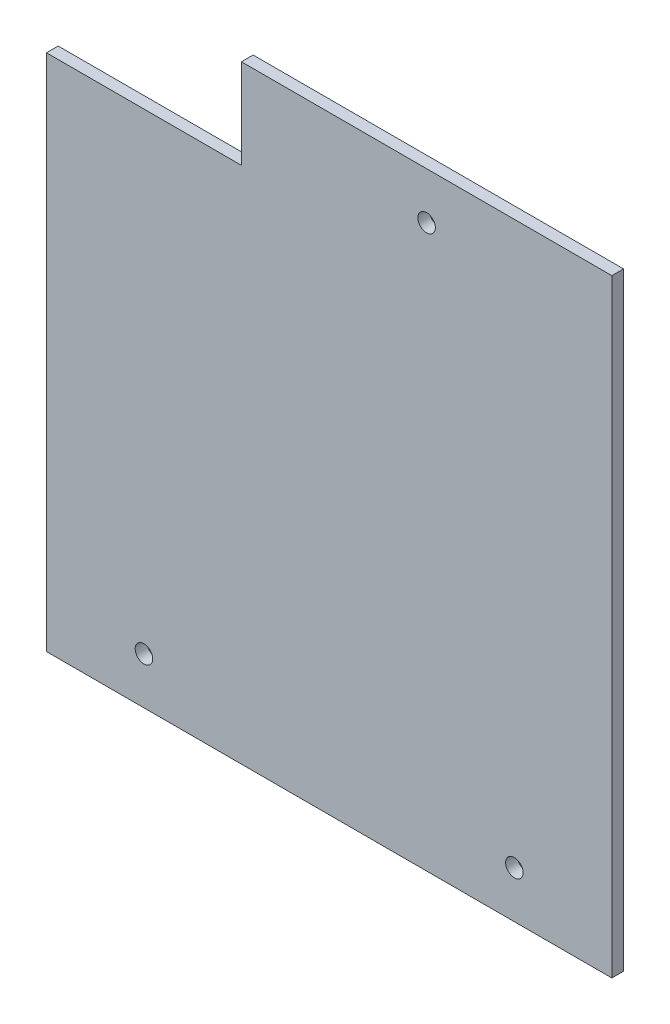
SolidWorks part; units mm, degrees
ref_plane "Ebene vorne" through (0, 0, 0) normal (0, 0, 1) x (1, 0, 0)
ref_plane "Ebene oben" through (0, 0, 0) normal (0, 1, 0) x (1, 0, 0)
ref_plane "Ebene rechts" through (0, 0, 0) normal (1, 0, 0) x (0, 0, -1)
sketch "Skizze1" plane through (0, 0, 0) normal (0, 0, 1) x (1, 0, 0)
  line L1 (72.5, -78) -> (-72.5, -78)
  line L2 (72.5, -78) -> (72.5, 78)
  line L3 (72.5, 78) -> (-72.5, 78)
  line L4 (-72.5, -78) -> (-72.5, 78)
  line L5 (72.5, -78) -> (-72.5, 78) construction
  line L6 (72.5, 78) -> (-72.5, -78) construction
  point P0 (0, 0)
  dimension "D1" = 156
  dimension "D2" = 145
extrude "Aufsatz-Linear austragen1" add sketch "Skizze1" along normal blind 3
hole_wizard "Durchgangsloch für M41" positions "Skizze2" profile "Skizze3" hole size "M4" standard "DIN"
sketch "Skizze2" plane through (0, 0, 3) normal (0, 0, 1) x (1, 0, 0)
  line L0 (-72.5, 78) -> (-72.5, -78) construction
  line L1 (72.5, 78) -> (-72.5, 78) construction
  line L3 (-72.5, -78) -> (72.5, -78) construction
  line L4 (72.5, -78) -> (72.5, 78) construction
  point P2 (25, 66)
  point P6 (-47.5, -66)
  point P25 (47.5, -66)
  dimension "D1" = 97.5
  dimension "D2" = 12
  dimension "D3" = 25
  dimension "D4" = 12
  dimension "D5" = 25
  dimension "D6" = 12
sketch "Skizze3" plane through (25, 66, 3) normal (1, 0, 0) x (0, -1, 0)
  line L0 (0, 0) -> (0, 4.3519)
  line L1 (0, 4.3519) -> (2.25, 3)
  line L2 (2.25, 3) -> (2.25, 0)
  line L5 (2.25, 0) -> (0, 0)
  line L10 (0, 4.3519) -> (-2.25, 3) construction
  line L11 (0, -6.35) -> (0, 107.95) construction
  dimension "Bohrerdurchmesser" = 4.5
  dimension "Bohrungstiefe" = 3
  dimension "Spitzenwinkel" = 118
sketch "Skizze5" plane through (0, 0, 0) normal (0, 0, -1) x (-1, 0, 0)
  line L1 (72.5, 78) -> (22.5, 78)
  line L2 (72.5, 78) -> (72.5, 55)
  line L3 (72.5, 55) -> (22.5, 55)
  line L4 (22.5, 78) -> (22.5, 55)
  dimension "D1" = 23
  dimension "D2" = 50
extrude "Schnitt-Linear austragen1" cut sketch "Skizze5" against normal through all
